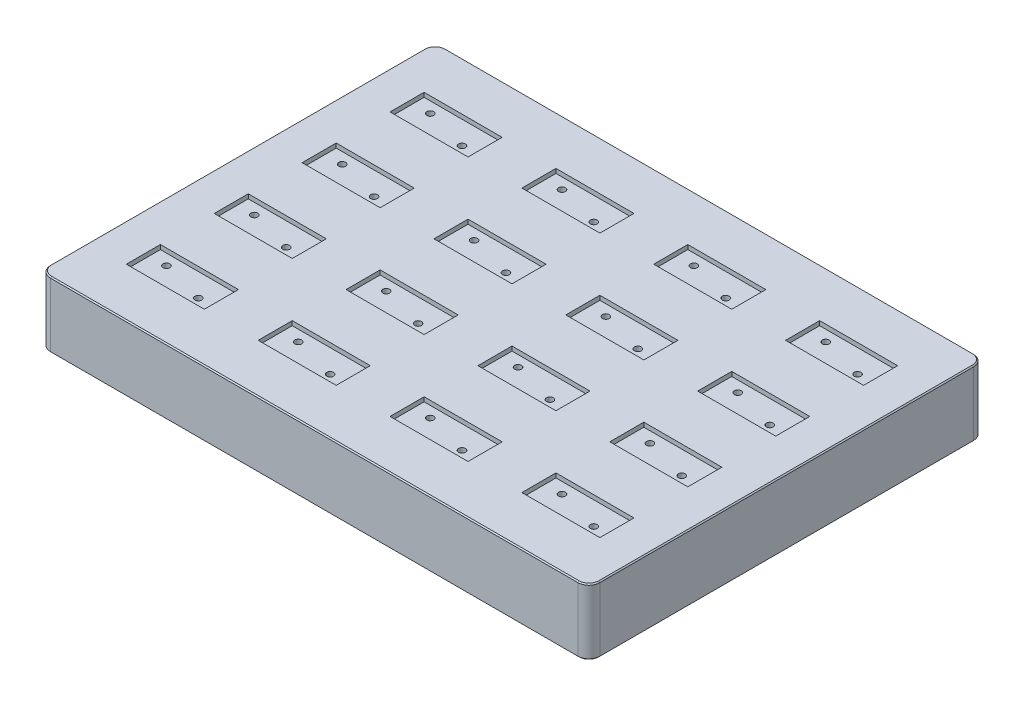
SolidWorks part; units mm, degrees
ref_plane "Front Plane" through (0, 0, 0) normal (0, 0, 1) x (1, 0, 0)
ref_plane "Top Plane" through (0, 0, 0) normal (0, 1, 0) x (1, 0, 0)
ref_plane "Right Plane" through (0, 0, 0) normal (1, 0, 0) x (0, 0, -1)
sketch "Sketch1" plane through (0, 0, 0) normal (0, 1, 0) x (1, 0, 0)
  line L1 (0, 0) -> (250, 0)
  line L2 (0, 0) -> (0, 180)
  line L3 (0, 180) -> (250, 180)
  line L4 (250, 0) -> (250, 180)
  dimension "D1" = 250
  dimension "D2" = 180
extrude "Boss-Extrude1" add sketch "Sketch1" along normal blind 30
sketch "Sketch2" plane through (0, 30, 0) normal (0, 1, 0) x (1, 0, 0)
  line L2 (0, 180) -> (0, 0) construction
  line L3 (17.25, 37.75) -> (52.75, 37.75)
  line L4 (17.25, 37.75) -> (17.25, 22.25)
  line L5 (17.25, 22.25) -> (52.75, 22.25)
  line L6 (52.75, 37.75) -> (52.75, 22.25)
  line L7 (0, 0) -> (250, 0) construction
  dimension "D1" = 15.5
  dimension "D2" = 35.5
  dimension "D3" = 17.25
  dimension "D4" = 22.25
extrude "Cut-Extrude1" cut sketch "Sketch2" against normal blind 2
pattern_linear "LPattern1" count 4 spacing 40 along (0, 0, -1) count 4 spacing 60 along (1, 0, 0) of "Cut-Extrude1"
sketch "Sketch3" plane through (0, 28, 0) normal (0, 1, 0) x (1, 0, 0)
  line L0 (35, 30) -> (35, 37.75) construction
  line L1 (52.75, 37.75) -> (17.25, 37.75) construction
  line L2 (52.75, 37.75) -> (17.25, 37.75) construction
  line L4 (17.25, 22.25) -> (52.75, 22.25) construction
  circle A0 centre (25, 32.75) radius 1.55
  circle A1 centre (45, 27.25) radius 1.55
  dimension "D1" = 3.1
  dimension "D2" = 20
  dimension "D3" = 5
  dimension "D4" = 5
  dimension "D5" = 10
extrude "Cut-Extrude2" cut sketch "Sketch3" against normal through all
pattern_linear "LPattern2" count 4 spacing 40 along (0, 0, -1) count 4 spacing 60 along (1, 0, 0) of "Cut-Extrude2"
sketch "Sketch4" plane through (0, 0, 0) normal (0, -1, 0) x (1, 0, 0)
  line L0 (0, -180) -> (0, 0) construction
  line L1 (3, -3) -> (247, -3)
  line L2 (3, -3) -> (3, -177)
  line L3 (3, -177) -> (247, -177)
  line L4 (247, -3) -> (247, -177)
  line L5 (250, -180) -> (0, -180) construction
  line L6 (250, 0) -> (250, -180) construction
  line L7 (0, 0) -> (250, 0) construction
  dimension "D1" = 3
  dimension "D2" = 3
  dimension "D3" = 3
  dimension "D4" = 3
extrude "Cut-Extrude3" cut sketch "Sketch4" against normal blind 23
fillet "Fillet1" radius 5 4 edges at (0, 15, -180) (0, 15, 0) (250, 15, 0) (250, 15, -180)
chamfer "Chamfer1" distance 0.5 angle 45 16 edges at (0, 0, -90) (1.4645, 0, -1.4645) (1.4645, 0, -178.5355) (125, 0, 0) (125, 0, -180) (248.5355, 0, -1.4645) (248.5355, 0, -178.5355) (250, 0, -90) (0, 30, -90) (1.4645, 30, -1.4645) (1.4645, 30, -178.5355) (125, 30, 0) (125, 30, -180) (248.5355, 30, -1.4645) (248.5355, 30, -178.5355) (250, 30, -90)
sketch "Sketch5" plane through (0, 0, -180) normal (0, 0, -1) x (-1, 0, 0)
  line L0 (0, 29.5) -> (0, 0.5) construction
  line L1 (-36.8, 5) -> (-24.3, 5)
  line L2 (-36.8, 5) -> (-36.8, 16.5)
  line L3 (-36.8, 16.5) -> (-24.3, 16.5)
  line L4 (-24.3, 5) -> (-24.3, 16.5)
  line L5 (-5, 0) -> (-245, 0) construction
  dimension "D1" = 12.5
  dimension "D2" = 11.5
  dimension "D3" = 24.3
  dimension "D4" = 5
extrude "Cut-Extrude4" cut sketch "Sketch5" against normal up to surface (3 mm away) up to face at (125, 11.5, -177)
fillet "Fillet2" radius 4 4 edges at (247, 11.5, -3) (247, 11.5, -177) (3, 11.5, -177) (3, 11.5, -3)
sketch "Sketch7" plane through (0, 23, 0) normal (0, -1, 0) x (1, 0, 0)
  line L0 (245, -180) -> (5, -180) construction
  line L1 (0, -175) -> (0, -5) construction
  circle A0 centre (17.78, -83.48) radius 3
  circle A1 centre (66.04, -77.13) radius 3
  circle A2 centre (60.96, -107.61) radius 3
  circle A3 centre (33.02, -107.61) radius 3
  circle A4 centre (17.78, -158.41) radius 3
  circle A5 centre (66.04, -159.68) radius 3
  dimension "D1" = 6
  dimension "D2" = 48.26
  dimension "D3" = 24.13
  dimension "D4" = 27.94
  dimension "D5" = 50.8
  dimension "D6" = 48.26
  dimension "D7" = 21.59
  dimension "D8" = 17.78
  dimension "D9" = 17.78
  dimension "D10" = 33.02
  dimension "D11" = 102.87
  dimension "D12" = 20.32
extrude "Boss-Extrude2" add sketch "Sketch7" along normal blind 5
fillet "Fillet3" radius 2 6 edges at (17.78, 23, -161.41) (66.04, 23, -162.68) (66.04, 23, -80.13) (60.96, 23, -110.61) (33.02, 23, -110.61) (17.78, 23, -86.48)
sketch "Sketch8" plane through (0, 18, 0) normal (0, -1, 0) x (1, 0, 0)
  circle A0 centre (17.78, -83.48) radius 1.3
  circle A1 centre (66.04, -77.13) radius 1.3
  circle A2 centre (60.96, -107.61) radius 1.3
  circle A3 centre (33.02, -107.61) radius 1.3
  circle A4 centre (17.78, -158.41) radius 1.3
  circle A5 centre (66.04, -159.68) radius 1.3
  dimension "D1" = 2.6
extrude "Cut-Extrude5" cut sketch "Sketch8" against normal blind 6
sketch "Sketch9" plane through (0, 0, -177) normal (0, 0, 1) x (1, 0, 0)
  line L4 (216.3, 17.35) -> (180.9, 17.35)
  line L5 (178.6349, 14.6506) -> (179.9697, 7.0806)
  line L6 (182.2348, 5.18) -> (214.9652, 5.18)
  line L7 (217.2303, 7.0806) -> (218.5651, 14.6506)
  circle A4 centre (222.1, 11.265) radius 1.6
  circle A5 centre (175.1, 11.265) radius 1.6
  arc A6 (180.9, 17.35) -> (178.6349, 14.6506) centre (180.9, 15.05) ccw
  arc A7 (179.9697, 7.0806) -> (182.2348, 5.18) centre (182.2348, 7.48) ccw
  arc A8 (214.9652, 5.18) -> (217.2303, 7.0806) centre (214.9652, 7.48) ccw
  arc A9 (218.5651, 14.6506) -> (216.3, 17.35) centre (216.3, 15.05) ccw
extrude "Cut-Extrude6" cut sketch "Sketch9" against normal up to surface (3 mm away) up to face at (30.55, 10.75, -180)
sketch "Sketch11" plane through (0, 23, 0) normal (0, -1, 0) x (1, 0, 0)
  line L0 (0.5, -90) -> (-8.3083, -90) construction
  line L1 (0.5, -5) -> (0.5, -175) construction
  line L2 (0, -175) -> (0, -5) construction
  line L3 (5, 0) -> (245, 0) construction
  line L4 (250, -5) -> (250, -175) construction
  line L5 (245, -180) -> (5, -180) construction
  line L6 (2.5, -90) -> (-6.231, -90) construction
  line L7 (125, -2.5) -> (125, 16.271) construction
  line L8 (125, -179.5) -> (125, -189.3502) construction
  line L9 (5, -179.5) -> (245, -179.5) construction
  circle A0 centre (7.5, -7.5) radius 5
  circle A1 centre (242.5, -7.5) radius 5
  circle A2 centre (242.5, -172.5) radius 5
  circle A3 centre (7.5, -172.5) radius 5
  circle A4 centre (125, -7.5) radius 5
  circle A5 centre (242.5, -90) radius 5
  circle A6 centre (7.5, -90) radius 5
  circle A7 centre (125, -172.5) radius 5
  dimension "D1" = 10
  dimension "D4" = 7.5
  dimension "D2" = 7.5
  dimension "D3" = 7.5
  dimension "D5" = 7.5
extrude "Boss-Extrude3" add sketch "Sketch11" along normal blind 21
sketch "Sketch12" plane through (0, 2, 0) normal (0, -1, 0) x (1, 0, 0)
  circle A0 centre (7.5, -90) radius 1.25
  circle A1 centre (7.5, -7.5) radius 1.25
  circle A2 centre (125, -7.5) radius 1.25
  circle A3 centre (242.5, -7.5) radius 1.25
  circle A4 centre (242.5, -90) radius 1.25
  circle A5 centre (242.5, -172.5) radius 1.25
  circle A6 centre (125, -172.5) radius 1.25
  circle A7 centre (7.5, -172.5) radius 1.25
  dimension "D1" = 2.5
extrude "Cut-Extrude7" cut sketch "Sketch12" against normal blind 10
fillet "Fillet4" radius 1 16 edges at (3, 12.5, -9.6794) (9.6794, 12.5, -3) (127.1794, 12.5, -3) (122.8206, 12.5, -3) (240.3206, 12.5, -3) (247, 12.5, -9.6794) (247, 12.5, -92.1794) (247, 12.5, -87.8206) (247, 12.5, -170.3206) (240.3206, 12.5, -177) (122.8206, 12.5, -177) (127.1794, 12.5, -177) (9.6794, 12.5, -177) (3, 12.5, -170.3206) (3, 12.5, -87.8206) (3, 12.5, -92.1794)
sketch "Sketch13" plane through (0, 0, -180) normal (0, 0, -1) x (-1, 0, 0)
  line L1 (-36.8, 16.5) -> (-24.3, 16.5)
  line L2 (-36.8, 16.5) -> (-36.8, 5)
  line L3 (-36.8, 5) -> (-24.3, 5)
  line L4 (-24.3, 16.5) -> (-24.3, 5)
extrude "Boss-Extrude4" add sketch "Sketch13" against normal blind 1 separate body
